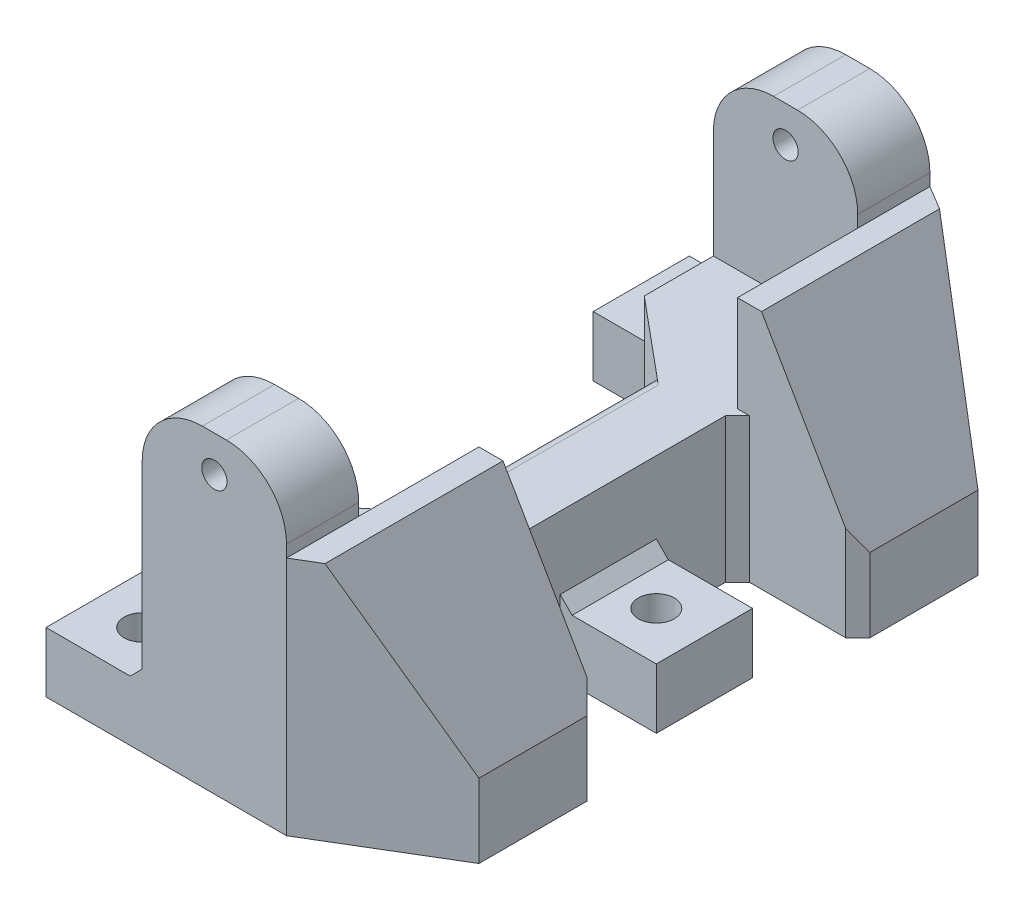
SolidWorks part; units mm, degrees
ref_plane "Спереди" through (0, 0, 0) normal (0, 0, 1) x (1, 0, 0)
ref_plane "Сверху" through (0, 0, 0) normal (0, 1, 0) x (1, 0, 0)
ref_plane "Справа" through (0, 0, 0) normal (1, 0, 0) x (0, 0, -1)
sketch "Эскиз1" plane through (0, 0, 0) normal (0, 1, 0) x (1, 0, 0)
  line L1 (0, 53.5) -> (-24, 53.5)
  line L2 (-24, 53.5) -> (-24, -53.5)
  line L3 (-24, -53.5) -> (0, -53.5)
  line L5 (0, 53.5) -> (0, -53.5)
  point P0 (0, 0)
  point P8 (0, 0)
  point P9 (0, 0)
  point P11 (0, 0)
  point P12 (0, 0)
  point P17 (0, 0)
  point P18 (0, 0)
  point P19 (0, 0)
  point P20 (0, 0)
extrude "Бобышка-Вытянуть1" add sketch "Эскиз1" along normal blind 15
ref_plane "Плоскость1" through (0, 15, 0) normal (0, 1, 0) x (1, 0, 0)
sketch "Эскиз2" plane through (0, 15, 0) normal (0, 1, 0) x (1, 0, 0)
  line L0 (0, 0) -> (0, 41.5)
  line L2 (0, 41.5) -> (-24, 41.5)
  line L4 (-24, 41.5) -> (-24, -41.5)
  line L5 (-24, -41.5) -> (0, -41.5)
  line L6 (0, -41.5) -> (0, 0)
  point P5 (0, 0)
  point P6 (0, 0)
  point P9 (0, 0)
  point P10 (0, 0)
  point P11 (0, 0)
extrude "Бобышка-Вытянуть2" add sketch "Эскиз2" along normal blind 9
sketch "Эскиз3" plane through (0, 0, 0) normal (0, 1, 0) x (1, 0, 0)
  line L0 (0, 41.5) -> (20, 41.5)
  line L1 (20, 41.5) -> (20, 21.5)
  line L2 (0, -41.5) -> (20, -41.5)
  line L4 (20, -41.5) -> (20, -21.5)
  line L5 (20, -21.5) -> (0, -21.5)
  line L6 (0, -41.5) -> (0, 41.5) construction
  line L7 (0, -21.5) -> (0, -41.5)
  line L8 (20, 21.5) -> (0, 21.5)
  line L9 (0, 21.5) -> (0, 41.5)
  line L10 (0, 41.5) -> (0, 53.5)
  line L11 (0, 53.5) -> (20, 41.5)
  line L12 (0, -41.5) -> (0, -53.5)
  line L14 (0, -53.5) -> (20, -41.5)
  point P6 (0, 0)
  point P16 (0, 0)
  point P19 (0, 0)
  point P20 (0, 0)
  point P21 (0, 0)
  point P22 (0, 0)
  point P23 (0, 0)
  point P24 (0, 0)
extrude "Бобышка-Вытянуть4" add sketch "Эскиз3" along normal blind 40 contours L11 L10 L0 | L9 L8 L1 L0 | L5 L7 L2 L4 | L12 L14 L2
sketch "Эскиз4" plane through (0, 15, 0) normal (0, 1, 0) x (1, 0, 0)
  line L0 (0, 41.5) -> (-24, 41.5)
  line L2 (-24, 41.5) -> (-24, 53.5)
  line L4 (-24, 53.5) -> (0, 53.5)
  line L6 (0, 53.5) -> (0, 41.5)
  line L12 (-24, -41.5) -> (0, -41.5)
  line L13 (0, -41.5) -> (0, -53.5)
  line L15 (0, -53.5) -> (-24, -53.5)
  line L17 (-24, -53.5) -> (-24, -41.5)
  point P5 (0, 0)
  point P6 (0, 0)
  point P9 (0, 0)
  point P10 (0, 0)
  point P12 (0, 0)
  point P22 (0, 0)
extrude "Бобышка-Вытянуть6" add sketch "Эскиз4" along normal blind 25
chamfer "Фаска2" distance 2 angle 45 4 edges at (20, 20, 21.5) (20, 20, -21.5) (0, 12, 21.5) (0, 12, -21.5)
sketch "Эскиз5" plane through (0, 0, 0) normal (0, 1, 0) x (1, 0, 0)
  line L0 (-24, 53.5) -> (-40, 53.5)
  line L1 (-40, 53.5) -> (-40, 37.5)
  line L2 (-40, 37.5) -> (-24, 37.5)
  line L4 (-24, 41.5) -> (-24, -41.5) construction
  line L5 (-24, 37.5) -> (-24, 53.5)
  line L6 (-24, -53.5) -> (-24, -37.5)
  line L7 (-24, -37.5) -> (-40, -37.5)
  line L8 (-40, -37.5) -> (-40, -53.5)
  line L9 (-40, -53.5) -> (-24, -53.5)
  line L10 (0, -8) -> (0, 8)
  line L11 (0, -19.5) -> (0, 19.5) construction
  line L12 (0, 8) -> (16, 8)
  line L13 (16, 8) -> (16, -8)
  line L14 (16, -8) -> (0, -8)
  circle A0 centre (-32, 45.5) radius 3
  circle A1 centre (-32, -45.5) radius 3
  circle A2 centre (8, 0) radius 3
  point P11 (0, 0)
  point P24 (0, 0)
  point P28 (0, 0)
  point P29 (0, 0)
  point P30 (0, 0)
  point P31 (0, 0)
  point P32 (0, 0)
  point P33 (0, 0)
extrude "Бобышка-Вытянуть7" add sketch "Эскиз5" along normal blind 10
chamfer "Фаска3" distance 2 angle 45 3 edges at (0, 10, 0) (-24, 10, 45.5) (-24, 10, -45.5)
ref_plane "Плоскость17" through (0, 0, -53.5) normal (0, 0, -1) x (-1, 0, 0)
sketch "Эскиз6" plane through (0, 0, -53.5) normal (0, 0, -1) x (-1, 0, 0)
  line L0 (24, 40) -> (24, 52)
  line L1 (24, 52) -> (0, 52)
  line L2 (0, 52) -> (0, 40)
  line L3 (0, 40) -> (24, 40)
  circle A0 centre (12, 46) radius 2.1
extrude "Бобышка-Вытянуть8" add sketch "Эскиз6" against normal blind 12
ref_plane "Плоскость18" through (0, 0, 53.5) normal (0, 0, 1) x (1, 0, 0)
sketch "Эскиз7" plane through (0, 0, 53.5) normal (0, 0, 1) x (1, 0, 0)
  line L0 (0, 40) -> (0, 52)
  line L1 (0, 52) -> (-24, 52)
  line L2 (-24, 52) -> (-24, 40)
  line L3 (-24, 40) -> (0, 40)
  circle A0 centre (-12, 46) radius 2.1
extrude "Бобышка-Вытянуть9" add sketch "Эскиз7" against normal blind 12
fillet "Скругление1" radius 10 4 edges at (0, 52, -47.5) (-24, 52, -47.5) (0, 52, 47.5) (-24, 52, 47.5)
chamfer "Фаска4" distance 16 angle 60 2 edges at (20, 40, 32.5) (20, 40, -32.5)
ref_plane "Плоскость19" through (0, 24, 0) normal (0, 1, 0) x (1, 0, 0)
sketch "Эскиз8" plane through (0, 24, 0) normal (0, 1, 0) x (1, 0, 0)
  line L0 (-24, 0) -> (-24, 30)
  line L1 (-24, 41.5) -> (-24, -41.5) construction
  line L3 (-12, 0) -> (-12, 20)
  line L4 (-12, 20) -> (-24, 30)
  line L5 (-24, 0) -> (-24, -30)
  line L6 (-12, 0) -> (-12, -20)
  line L7 (-12, -20) -> (-24, -30)
extrude "Вырез-Вытянуть1" cut sketch "Эскиз8" against normal blind 12
fillet "Скругление2" radius 2 2 edges at (-12, 24, 0) (-24, 12, 0)
